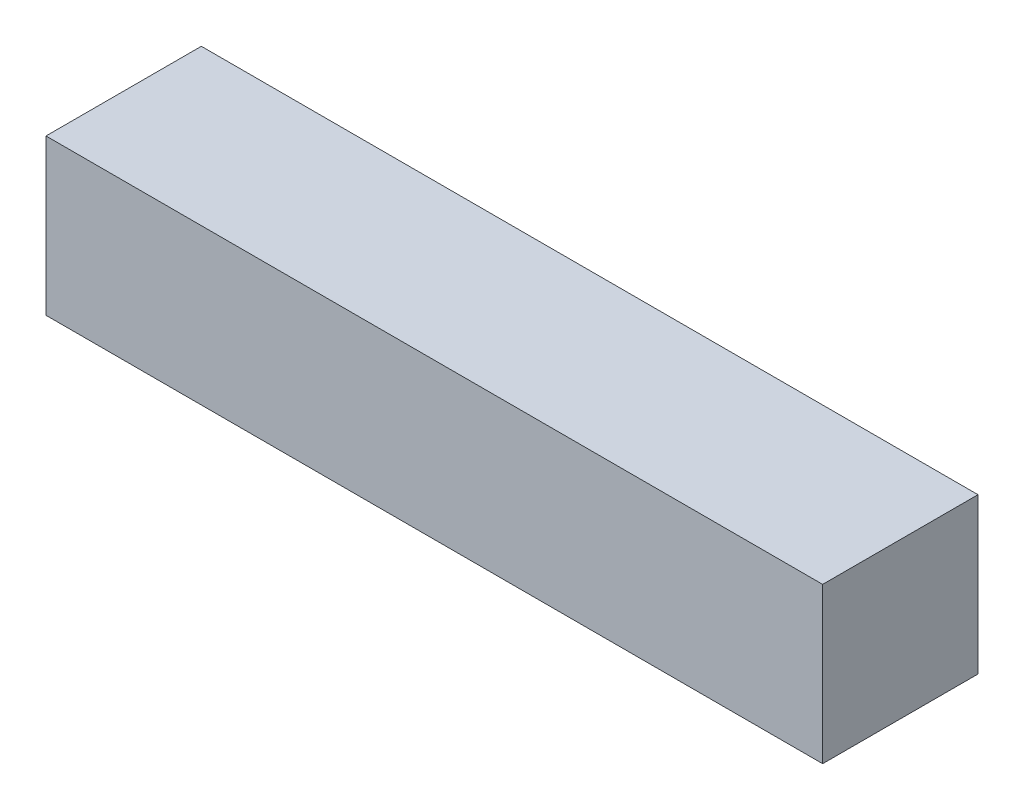
SolidWorks part; units mm, degrees
ref_plane "Front Plane" through (0, 0, 0) normal (1, 0, 0) x (0, 1, 0)
ref_plane "Top Plane" through (0, 0, 0) normal (0, 0, 1) x (0, 1, 0)
ref_plane "Right Plane" through (0, 0, 0) normal (0, 1, 0) x (-1, 0, 0)
sketch "Sketch1" plane through (0, 0, 0) normal (0, 0, 1) x (0, 1, 0)
  line L1 (-6, 18.0732) -> (0, 18.0732)
  line L2 (-6, 18.0732) -> (-6, -11.9268)
  line L3 (-6, -11.9268) -> (0, -11.9268)
  line L4 (0, 18.0732) -> (0, -11.9268)
  dimension "D1" = 6
  dimension "D2" = 30
extrude "Boss-Extrude1" add sketch "Sketch1" along normal blind 6
